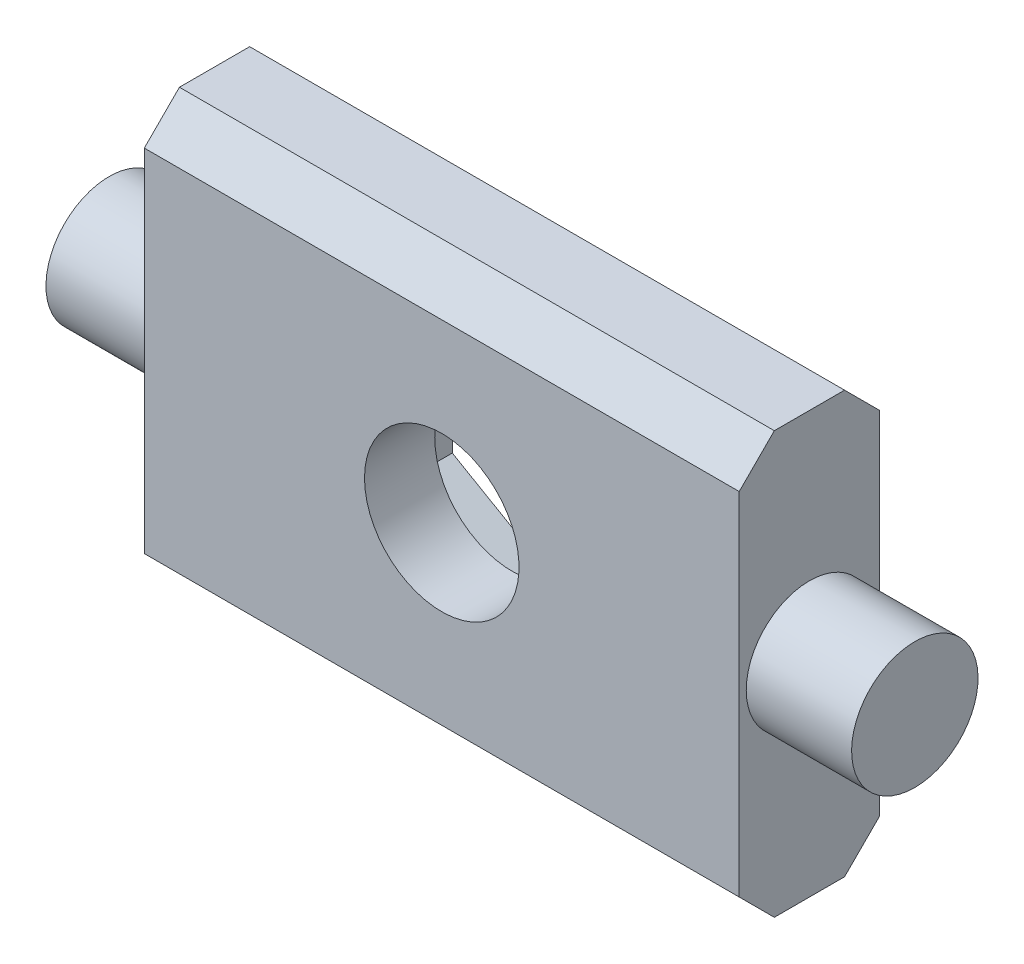
SolidWorks part; units mm, degrees
ref_plane "Спереди" through (0, 0, 0) normal (0, 0, 1) x (1, 0, 0)
ref_plane "Сверху" through (0, 0, 0) normal (0, 1, 0) x (1, 0, 0)
ref_plane "Справа" through (0, 0, 0) normal (1, 0, 0) x (0, 0, -1)
sketch "Эскиз1" plane through (0, 0, 0) normal (0, 0, 1) x (1, 0, 0)
  line L1 (-11.47, 6) -> (11.47, 6)
  line L2 (-11.47, 6) -> (-11.47, -6)
  line L3 (-11.47, -6) -> (11.47, -6)
  line L4 (11.47, 6) -> (11.47, -6)
  line L5 (-11.47, 6) -> (11.47, -6) construction
  line L6 (-11.47, -6) -> (11.47, 6) construction
  point P0 (0, 0)
  dimension "D1" = 12
  dimension "D2" = 22.94
extrude "Бобышка-Вытянуть1" add sketch "Эскиз1" along normal blind 4
sketch "Эскиз3" plane through (11.47, 0, 0) normal (1, 0, 0) x (0, 0, -1)
  line L1 (0, -6) -> (-4, -6)
  line L2 (-4, 6) -> (0, 6)
  line L3 (-4, 6) -> (-4, -6)
  line L4 (-4, -6) -> (0, -6)
  line L5 (0, 6) -> (0, -6)
  circle A0 centre (-2, 0) radius 2
  line M1 (0, -6) -> (0, 6)
  line M2 (0, 6) -> (-4, 6)
  line M3 (-4, 6) -> (-4, -6)
  line M4 (-4, -6) -> (0, -6)
  dimension "D1" = 4
extrude "Вырез-Вытянуть1" cut sketch "Эскиз3" against normal blind 3 contours A0 L5 M2 M3 | A0 L3 M4 M1
sketch "Эскиз4" plane through (-11.47, 0, 0) normal (-1, 0, 0) x (0, 0, 1)
  line L1 (0, 6) -> (4, 6)
  line L2 (0, 6) -> (0, -6)
  line L3 (0, -6) -> (4, -6)
  line L4 (4, 6) -> (4, -6)
  circle A0 centre (2, 0) radius 2
  line M1 (0, 6) -> (0, -6)
  line M2 (0, -6) -> (4, -6)
  line M3 (4, -6) -> (4, 6)
  line M4 (4, 6) -> (0, 6)
  dimension "D1" = 4
extrude "Вырез-Вытянуть2" cut sketch "Эскиз4" against normal blind 3 contours A0 L4 M4 M1 | A0 L2 M2 M3
sketch "Эскиз5" plane through (0, 0, 0) normal (0, 0, -1) x (-1, 0, 0)
  line L1 (0, -4.0415) -> (3.5, -2.0207)
  line L2 (3.5, -2.0207) -> (3.5, 2.0207)
  line L3 (3.5, 2.0207) -> (0, 4.0415)
  line L4 (0, 4.0415) -> (-3.5, 2.0207)
  line L5 (-3.5, 2.0207) -> (-3.5, -2.0207)
  line L6 (-3.5, -2.0207) -> (0, -4.0415)
  circle A0 centre (0, 0) radius 3.5 construction
  dimension "D1" = 7
extrude "Вырез-Вытянуть4" cut sketch "Эскиз5" against normal blind 2
sketch "Эскиз6" plane through (0, 0, 0) normal (0, 0, -1) x (-1, 0, 0)
  circle A0 centre (0, 0) radius 2
  dimension "D1" = 4
extrude "Вырез-Вытянуть5" cut sketch "Эскиз6" against normal through all
chamfer "Фаска1" distance 1 angle 45 1 edges at (0, 6, 0)
chamfer "Фаска2" distance 1 angle 45 3 edges at (0, -6, 4) (0, -6, 0) (0, 6, 4)
sketch "Эскиз7" plane through (8.47, 0, 0) normal (1, 0, 0) x (0, 0, -1)
  circle A0 centre (-2, 0) radius 1.8
  circle A1 centre (-2, 0) radius 2
  dimension "D1" = 3.6
extrude "Вырез-Вытянуть6" cut sketch "Эскиз7" along normal blind 10
sketch "Эскиз8" plane through (-11.47, 0, 0) normal (-1, 0, 0) x (0, 0, 1)
  circle A0 centre (2, 0) radius 2
  circle A1 centre (2, 0) radius 1.8
  dimension "D1" = 3.6
extrude "Вырез-Вытянуть7" cut sketch "Эскиз8" against normal up to vertex (3 mm away) up to point (-8.47, 5, 4)
sketch "Эскиз9" plane through (0, 0, 0) normal (0, 0, -1) x (-1, 0, 0)
  circle A0 centre (0, 0) radius 2.2
  dimension "D1" = 4.4
extrude "Вырез-Вытянуть8" cut sketch "Эскиз9" against normal through all
sketch "Эскиз10" plane through (0, 0, 0) normal (0, 0, -1) x (-1, 0, 0)
  line L1 (0, -4.2724) -> (3.7, -2.1362)
  line L2 (3.7, -2.1362) -> (3.7, 2.1362)
  line L3 (3.7, 2.1362) -> (0, 4.2724)
  line L4 (0, 4.2724) -> (-3.7, 2.1362)
  line L5 (-3.7, 2.1362) -> (-3.7, -2.1362)
  line L6 (-3.7, -2.1362) -> (0, -4.2724)
  circle A0 centre (0, 0) radius 3.7 construction
  dimension "D1" = 7.4
extrude "Вырез-Вытянуть9" cut sketch "Эскиз10" against normal up to surface (2 mm away) up to face at (-2.2, 0, 2)
